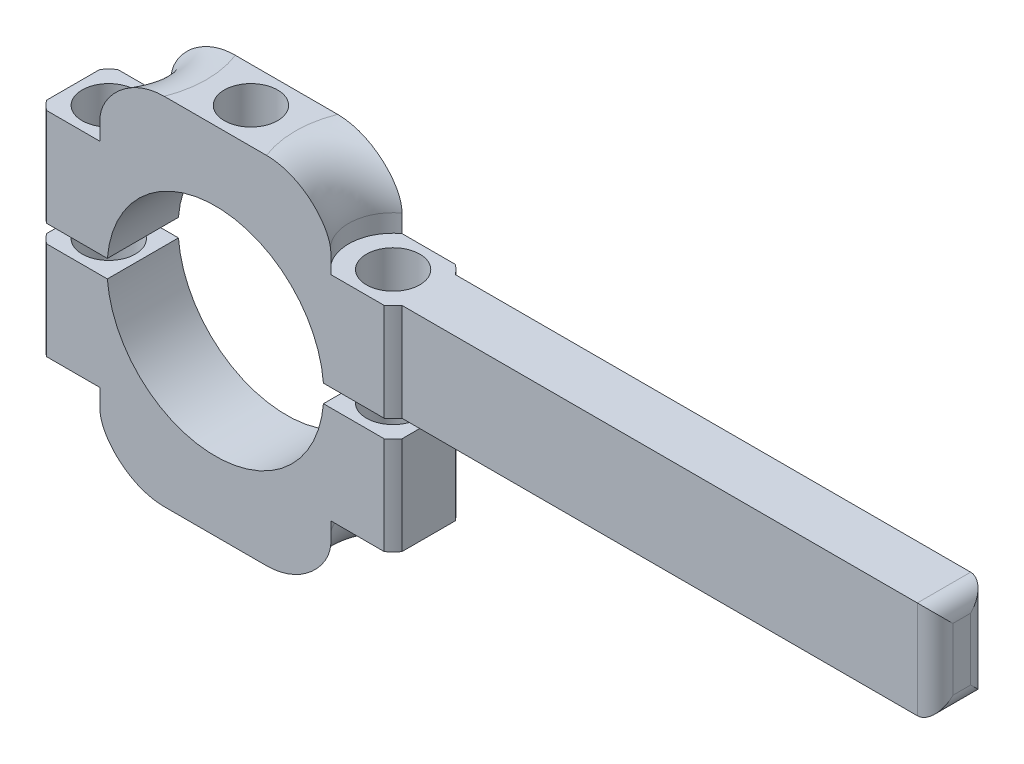
SolidWorks part; units mm, degrees
ref_plane "Front Plane" through (0, 0, 0) normal (0, 0, 1) x (1, 0, 0)
ref_plane "Top Plane" through (0, 0, 0) normal (0, 1, 0) x (1, 0, 0)
ref_plane "Right Plane" through (0, 0, 0) normal (1, 0, 0) x (0, 0, -1)
sketch "Sketch1" plane through (0, 0, 0) normal (0, 0, 1) x (1, 0, 0)
  line L1 (-10, -10) -> (10, -10)
  line L2 (-10, -10) -> (-10, 10)
  line L3 (-10, 10) -> (10, 10)
  line L4 (10, -10) -> (10, 10)
  line L5 (-10, -10) -> (10, 10) construction
  line L6 (-10, 10) -> (10, -10) construction
  line L7 (-10, -0.5) -> (-6.0795, -0.5)
  line L8 (-10, -0.5) -> (-10, 0.5)
  line L9 (-10, 0.5) -> (-6.0795, 0.5)
  line L10 (-6.0795, -0.5) -> (-6.0795, 0.5)
  line L11 (6.0795, -0.5) -> (10, -0.5)
  line L12 (6.0795, -0.5) -> (6.0795, 0.5)
  line L13 (6.0795, 0.5) -> (10, 0.5)
  line L14 (10, -0.5) -> (10, 0.5)
  circle A0 centre (0, 0) radius 6.1
  point P0 (0, 0)
  point P12 (6.0795, 0)
  point P13 (-6.0795, 0)
  dimension "D3" = 12.2
  dimension "D1" = 20
  dimension "D2" = 20
  dimension "D4" = 1
  dimension "D5" = 1
extrude "Boss-Extrude1" add sketch "Sketch1" along normal blind 4 contours A0 L7 L2 L1 L4 L11 | A0 L13 L4 L3 L2 L9
sketch "Sketch2" plane through (0, 0, 0) normal (0, 1, 0) x (1, 0, 0)
  line L0 (10, -4) -> (10, 0) construction
  line L1 (-10, -4) -> (-10, 0) construction
  line L2 (0, 5.2223) -> (0, -8.4062) construction
  line L3 (-2.6121, 0) -> (-2.6121, -4)
  line L4 (-14.9471, -1.5628) -> (14.9628, -1.5628) construction
  line L5 (-10, 0) -> (10, 0) construction
  line L6 (-10, -4) -> (10, -4) construction
  circle A0 centre (8, -2) radius 2.5
  circle A1 centre (-8, -2) radius 2.5
  circle A2 centre (8, -2) radius 1.5
  circle A3 centre (-8, -2) radius 1.5
  point P21 (0, 0)
  point P22 (0, 0)
  dimension "D1" = 5
  dimension "D2" = 5
  dimension "D3" = 3
  dimension "D4" = 3
  dimension "D6" = 2
  dimension "D5" = 2
  dimension "D7" = 2
extrude "Cut-Extrude1" cut sketch "Sketch2" along direction (0, 1, 0) on the side of the normal blind 4 from surface at -10 contours A1 | A0 | A3 starting at face at (0, -10, 2)
sketch "Sketch3" plane through (0, 0, 0) normal (0, 1, 0) x (1, 0, 0)
  line L0 (0, 0) -> (0, -4)
  line L1 (-10, 0) -> (10, 0) construction
  line L2 (-10, -4) -> (-10, 0) construction
  line L3 (10, -4) -> (10, 0) construction
  circle A0 centre (8, -2) radius 2.5
  circle A1 centre (-8, -2) radius 2.5
  circle A2 centre (8, -2) radius 1.5
  circle A3 centre (-8, -2) radius 1.5
  point P8 (0, 0)
  point P11 (0, 0)
  point P12 (0, 0)
  point P13 (0, -2)
  dimension "D1" = 5
  dimension "D2" = 5
  dimension "D3" = 3
  dimension "D4" = 3
  dimension "D5" = 2
  dimension "D6" = 2
  dimension "D7" = 4
extrude "Cut-Extrude2" cut sketch "Sketch3" against normal blind 4 from surface at 10 contours A1 A3 | A0 A2 starting at face at (0, 10, 2)
sketch "Sketch4" plane through (0, 10, 0) normal (0, 1, 0) x (1, 0, 0)
  line L0 (-10, -3.5) -> (-10, -4) construction
  line L1 (-10, -4) -> (-9.5, -4) construction
  line L2 (-9.5, 0) -> (-10, 0) construction
  line L3 (-10, 0) -> (-10, -0.5) construction
  line L4 (10, -0.5) -> (10, 0) construction
  line L5 (10, 0) -> (9.5, 0) construction
  line L6 (9.5, -4) -> (10, -4) construction
  line L7 (10, -4) -> (10, -3.5) construction
  line L8 (-10, -3.5) -> (-10, -4)
  line L9 (-10, -4) -> (-9.5, -4)
  line L10 (-9.5, 0) -> (-10, 0)
  line L11 (-10, 0) -> (-10, -0.5)
  line L12 (10, -0.5) -> (10, 0)
  line L13 (10, 0) -> (9.5, 0)
  line L14 (9.5, -4) -> (10, -4)
  line L15 (10, -4) -> (10, -3.5)
  circle A0 centre (8, -2) radius 1.5 construction
  circle A1 centre (-8, -2) radius 1.5 construction
  circle A2 centre (8, -2) radius 1.5
  circle A3 centre (-8, -2) radius 1.5
  arc A4 (-10, -3.5) -> (-9.5, -4) centre (-8, -2) ccw construction
  arc A5 (-9.5, 0) -> (-10, -0.5) centre (-8, -2) ccw construction
  arc A6 (10, -0.5) -> (9.5, 0) centre (8, -2) ccw construction
  arc A7 (9.5, -4) -> (10, -3.5) centre (8, -2) ccw construction
  arc A8 (-10, -3.5) -> (-9.5, -4) centre (-8, -2) ccw
  arc A9 (-9.5, 0) -> (-10, -0.5) centre (-8, -2) ccw
  arc A10 (10, -0.5) -> (9.5, 0) centre (8, -2) ccw
  arc A11 (9.5, -4) -> (10, -3.5) centre (8, -2) ccw
extrude "Cut-Extrude3" cut sketch "Sketch4" against normal through all
sketch "Sketch5" plane through (0, 10, 0) normal (0, 1, 0) x (1, 0, 0)
  line L0 (-6.5, -4) -> (6.5, -4) construction
  circle A0 centre (0, -2) radius 1.5
  point P5 (0, 0)
  dimension "D1" = 3
  dimension "D2" = 2
extrude "Cut-Extrude4" cut sketch "Sketch5" against normal blind 6
fillet "Fillet1" radius 3 2 edges at (5.5, 10, 2) (-5.5, 10, 2)
fillet "Fillet2" radius 3 2 edges at (5.5, -10, 2) (-5.5, -10, 2)
sketch "Sketch6" plane through (10, 0, 0) normal (1, 0, 0) x (0, 0, -1)
  line L0 (0, 6) -> (-0.5, 6) construction
  line L1 (0, 0.5) -> (0, 6) construction
  line L2 (-4, 0.5) -> (-4, 6) construction
  line L3 (-3.5, 6) -> (-4, 6) construction
  line L5 (-0.5, 0.5) -> (0, 0.5) construction
  line L6 (-4, 0.5) -> (-3.5, 0.5) construction
  line L7 (0, 6) -> (-0.5, 6)
  line L8 (-4, 0.5) -> (-3.5, 0.5)
  line L9 (-0.5, 0.5) -> (0, 0.5)
  line L10 (-3.5, 6) -> (-4, 6)
  line L11 (-3.5, 0.5) -> (-0.5, 0.5)
  line L12 (-0.5, 0.5) -> (-0.5, 6)
  line L13 (-0.5, 6) -> (-3.5, 6)
  line L14 (-3.5, 6) -> (-3.5, 0.5)
  line L15 (-3.5, 0.5) -> (-0.5, 0.5)
  line L16 (-0.5, 0.5) -> (-0.5, 6)
  line L17 (-0.5, 6) -> (-3.5, 6)
  line L18 (-3.5, 6) -> (-3.5, 0.5)
  line L19 (-4, 0.5) -> (-4, 6)
  line L20 (0, 0.5) -> (0, 6)
  dimension "D1" = 0
extrude "Boss-Extrude2" add sketch "Sketch6" along normal blind 30 contours L15 L16 L17 L18
fillet "Fillet3" radius 1 4 edges at (40, 6, 2) (40, 3.25, 0.5) (40, 0.5, 2) (40, 3.25, 3.5)
